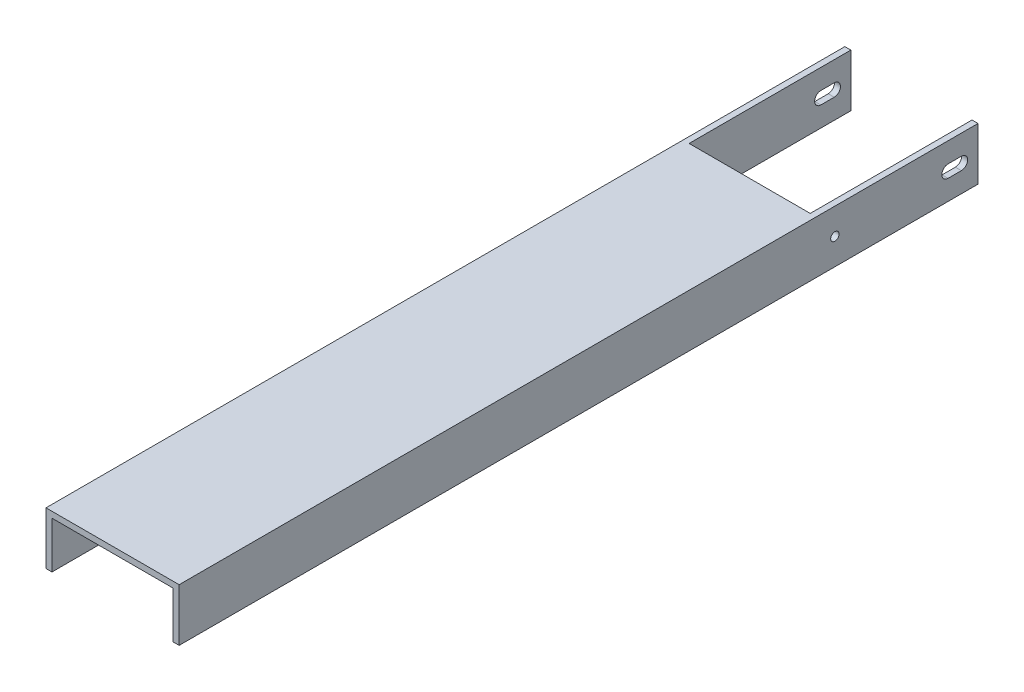
SolidWorks part; units mm, degrees
ref_plane "Front Plane" through (0, 0, 0) normal (0, 0, 1) x (1, 0, 0)
ref_plane "Top Plane" through (0, 0, 0) normal (0, 1, 0) x (1, 0, 0)
ref_plane "Right Plane" through (0, 0, 0) normal (1, 0, 0) x (0, 0, -1)
sketch "Sketch1" plane through (0, 0, 0) normal (0, 0, 1) x (1, 0, 0)
  line L0 (-50.8, 0) -> (50.8, 0)
  line L1 (50.8, 0) -> (50.8, -40.132)
  line L2 (50.8, -40.132) -> (46.228, -40.132)
  line L3 (46.228, -40.132) -> (46.228, -4.572)
  line L4 (46.228, -4.572) -> (-46.228, -4.572)
  line L5 (-46.228, -4.572) -> (-46.228, -40.132)
  line L6 (-46.228, -40.132) -> (-50.8, -40.132)
  line L7 (-50.8, -40.132) -> (-50.8, 0)
  point P8 (0, 0)
  dimension "D1" = 40.132
  dimension "D2" = 4.572
  dimension "D3" = 4.572
  dimension "D4" = 101.6
extrude "Boss-Extrude1" add sketch "Sketch1" along normal blind 609.6
sketch "Sketch3" plane through (0, 0, 0) normal (0, 1, 0) x (1, 0, 0)
  line L0 (50.8, 0) -> (-50.8, 0) construction
  line L1 (-46.228, -123.444) -> (46.228, -123.444)
  line L2 (-46.228, -123.444) -> (-46.228, 0)
  line L3 (-46.228, 0) -> (46.228, 0)
  line L4 (46.228, -123.444) -> (46.228, 0)
  line L5 (-46.228, -123.444) -> (46.228, 0) construction
  line L6 (-46.228, 0) -> (46.228, -123.444) construction
  line L7 (-46.228, -609.6) -> (-46.228, 0) construction
  line L8 (46.228, -609.6) -> (46.228, 0) construction
  point P0 (0, -61.722)
  dimension "D1" = 123.444
extrude "Cut-Extrude1" cut sketch "Sketch3" against normal through all
sketch "Sketch4" plane through (50.8, 0, 0) normal (1, 0, 0) x (0, 0, -1)
  line L0 (-12.7, -20.066) -> (-22.86, -20.066) construction
  line L1 (-12.7, -24.8285) -> (-22.86, -24.8285)
  line L2 (-12.7, -15.3035) -> (-22.86, -15.3035)
  line L3 (0, -40.132) -> (0, 0) construction
  arc A0 (-12.7, -24.8285) -> (-12.7, -15.3035) centre (-12.7, -20.066) ccw
  arc A1 (-22.86, -15.3035) -> (-22.86, -24.8285) centre (-22.86, -20.066) ccw
  circle A2 centre (-109.22, -20.066) radius 3.175
  point P3 (-17.78, -20.066)
  point P10 (0, -20.066)
  dimension "D3" = 9.525
  dimension "D5" = 6.35
  dimension "D1" = 10.16
  dimension "D2" = 12.7
  dimension "D4" = 109.22
extrude "Cut-Extrude2" cut sketch "Sketch4" against normal through all
